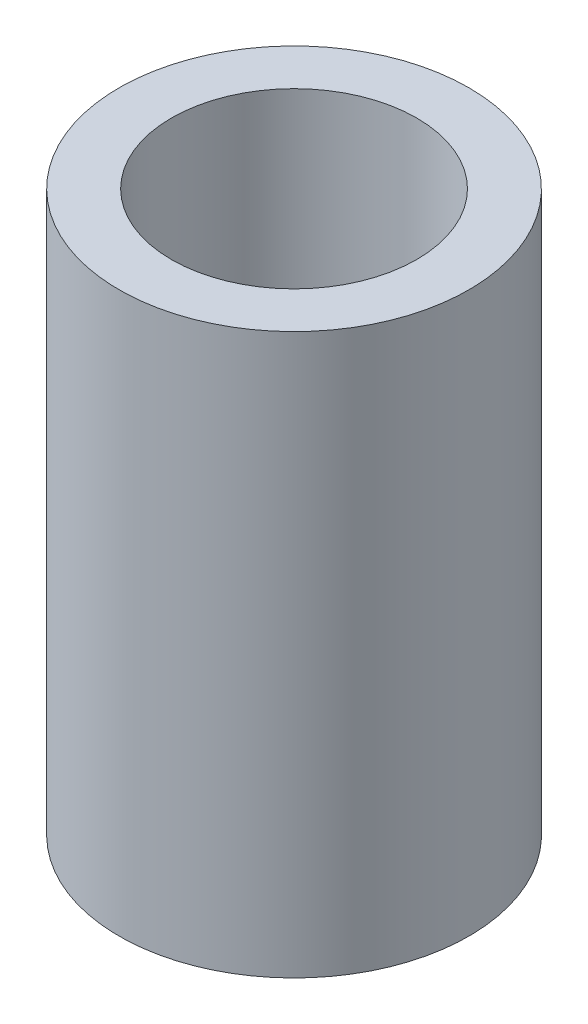
SolidWorks part; units mm, degrees
ref_plane "Front Plane" through (0, 0, 0) normal (0, 0, 1) x (1, 0, 0)
ref_plane "Top Plane" through (0, 0, 0) normal (0, 1, 0) x (1, 0, 0)
ref_plane "Right Plane" through (0, 0, 0) normal (1, 0, 0) x (0, 0, -1)
sketch "Sketch1" plane through (0, 0, 0) normal (0, 0, 1) x (1, 0, 0)
  line L0 (2.5, 8) -> (1.7526, 8)
  line L1 (1.7526, 8) -> (1.7526, 0)
  line L2 (1.7526, 0) -> (2.5, 0)
  line L3 (2.5, 0) -> (2.5, 8)
  line L4 (0, 8) -> (0, 0) construction
revolve "Revolve1" add sketch "Sketch1" angle 360 about L4
